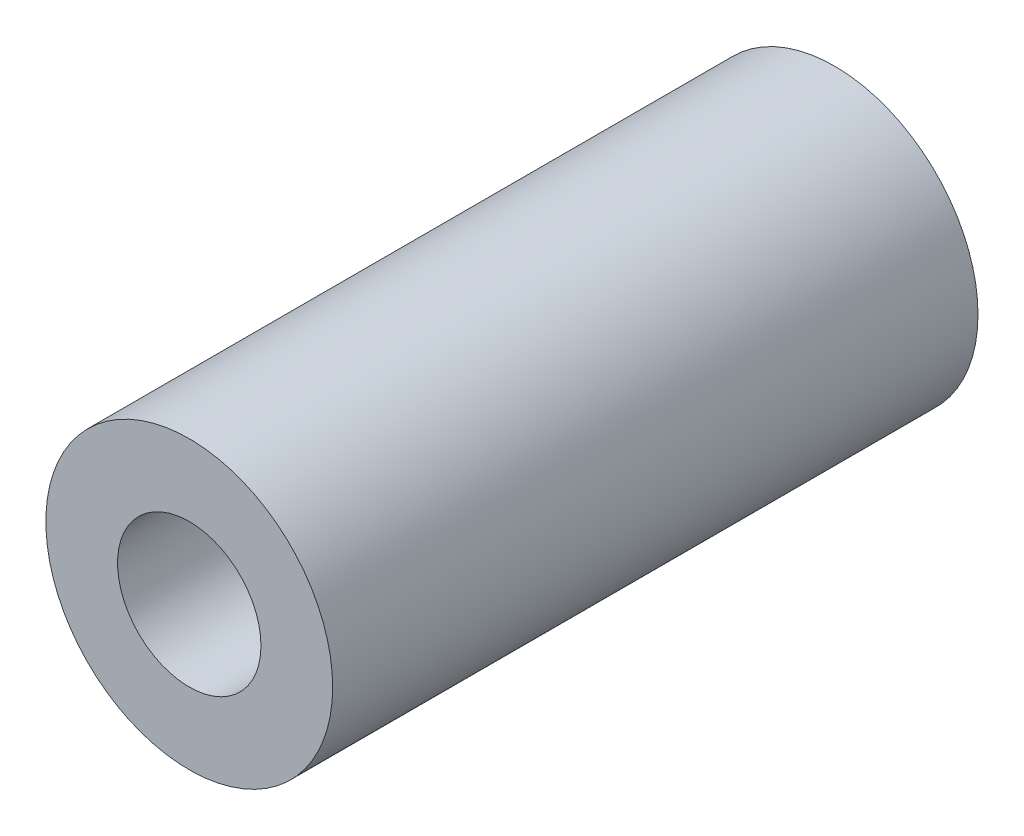
SolidWorks part; units mm, degrees
ref_plane "Front Plane" through (0, 0, 0) normal (0, 0, 1) x (1, 0, 0)
ref_plane "Top Plane" through (0, 0, 0) normal (0, 1, 0) x (1, 0, 0)
ref_plane "Right Plane" through (0, 0, 0) normal (1, 0, 0) x (0, 0, -1)
sketch "Sketch1" plane through (0, 0, 0) normal (0, 0, 1) x (1, 0, 0)
  circle A0 centre (0, 0) radius 4
  circle A1 centre (0, 0) radius 2
  dimension "D1" = 4
  dimension "D2" = 8
extrude "Boss-Extrude1" add sketch "Sketch1" along normal blind 18
